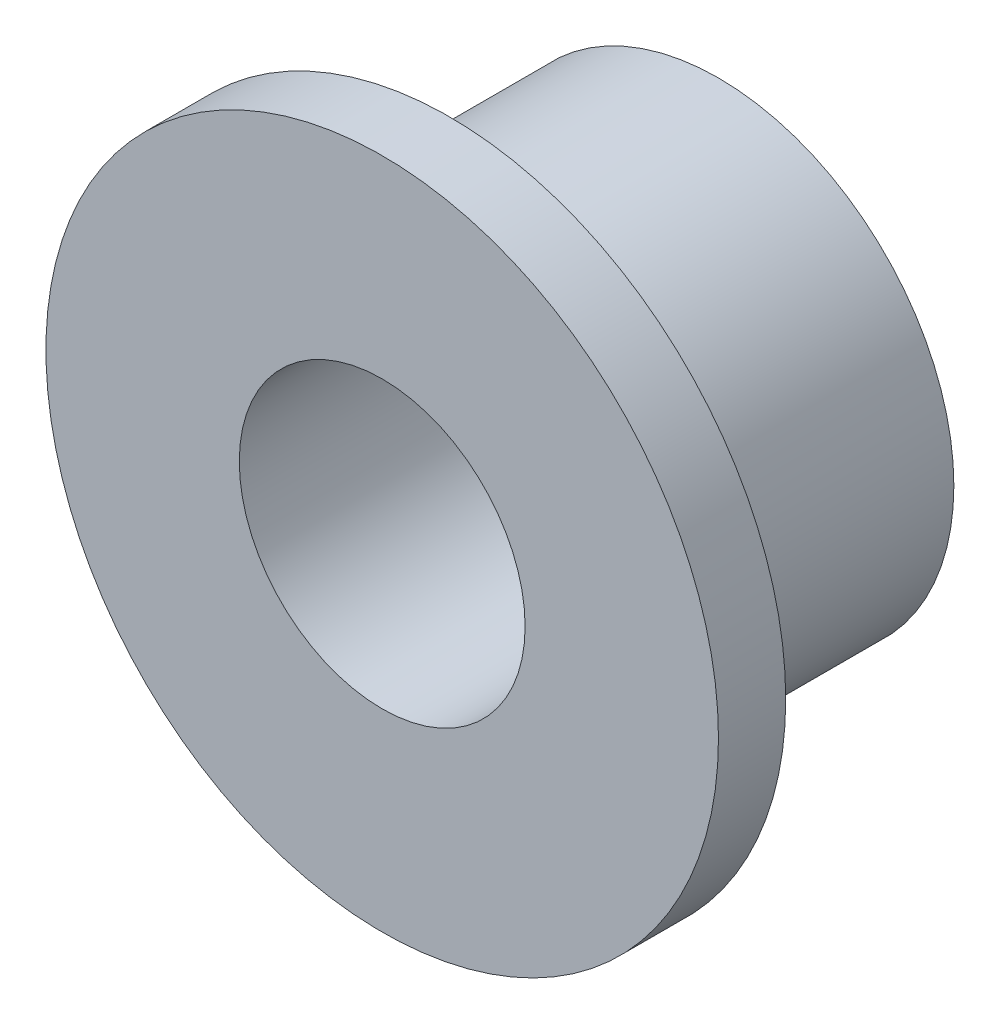
SolidWorks part; units mm, degrees
material "AISI 1035 Steel (SS)"
ref_plane "Front Plane" through (0, 0, 0) normal (0, 0, 1) x (1, 0, 0)
ref_plane "Top Plane" through (0, 0, 0) normal (0, 1, 0) x (1, 0, 0)
ref_plane "Right Plane" through (0, 0, 0) normal (1, 0, 0) x (0, 0, -1)
sketch "Sketch1" plane through (0, 0, 0) normal (0, 0, 1) x (1, 0, 0)
  circle A0 centre (0, 0) radius 7
  circle A1 centre (0, 0) radius 4.25
  dimension "D1" = 8.5
  dimension "D2" = 14
extrude "Boss-Extrude1" add sketch "Sketch1" along normal blind 10
sketch "Sketch2" plane through (0, 0, 10) normal (0, 0, 1) x (1, 0, 0)
  circle A0 centre (0, 0) radius 10
  circle A1 centre (0, 0) radius 7 construction
  circle A2 centre (0, 0) radius 7
  dimension "D1" = 20
extrude "Boss-Extrude2" add sketch "Sketch2" against normal blind 2
